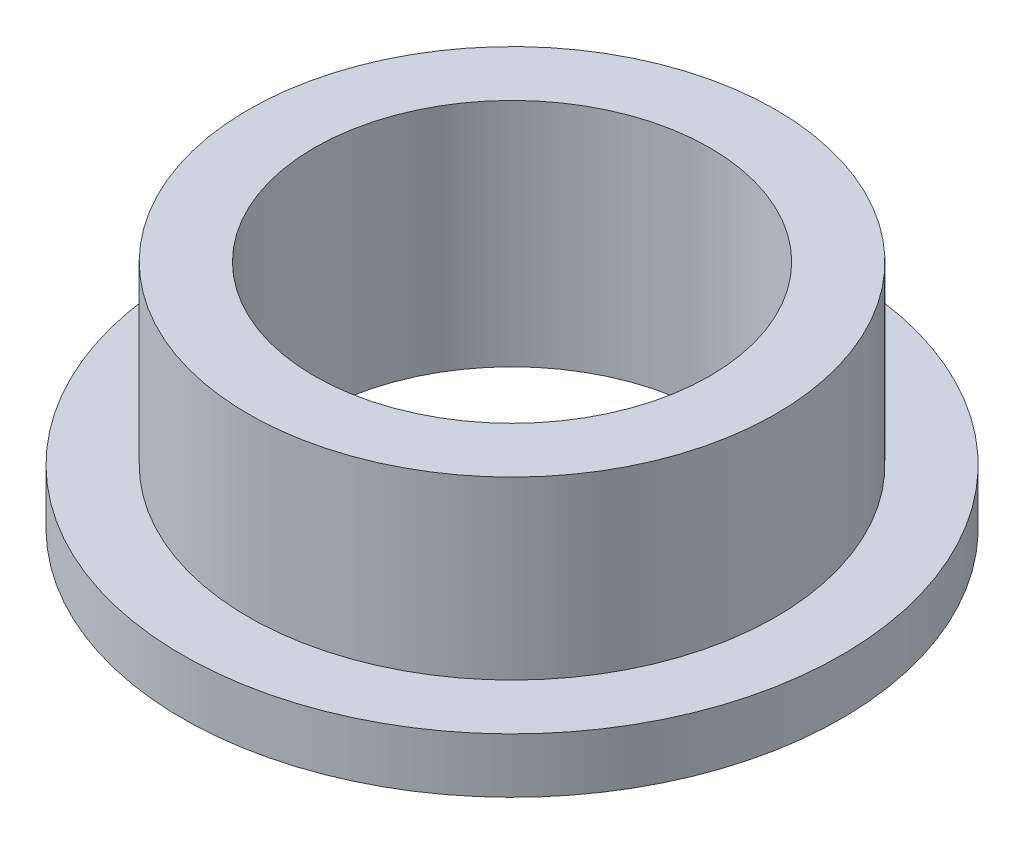
SolidWorks part; units mm, degrees
ref_plane "Front Plane" through (0, 0, 0) normal (0, 0, 1) x (1, 0, 0)
ref_plane "Top Plane" through (0, 0, 0) normal (0, 1, 0) x (1, 0, 0)
ref_plane "Right Plane" through (0, 0, 0) normal (1, 0, 0) x (0, 0, -1)
sketch "Sketch1" plane through (0, 0, 0) normal (0, 0, 1) x (1, 0, 0)
  line L0 (0, 0) -> (0, 18.0472) construction
  line L1 (18, 0) -> (18, 21)
  line L2 (18, 21) -> (24, 21)
  line L3 (24, 21) -> (24, 5)
  line L4 (24, 5) -> (30, 5)
  line L5 (30, 5) -> (30, 0)
  line L6 (30, 0) -> (18, 0)
  point P5 (0, 0)
  dimension "D1" = 16
  dimension "D2" = 21
  dimension "D3" = 30
  dimension "D4" = 24
  dimension "D5" = 18
revolve "Revolve1" add sketch "Sketch1" angle 360 about L0
